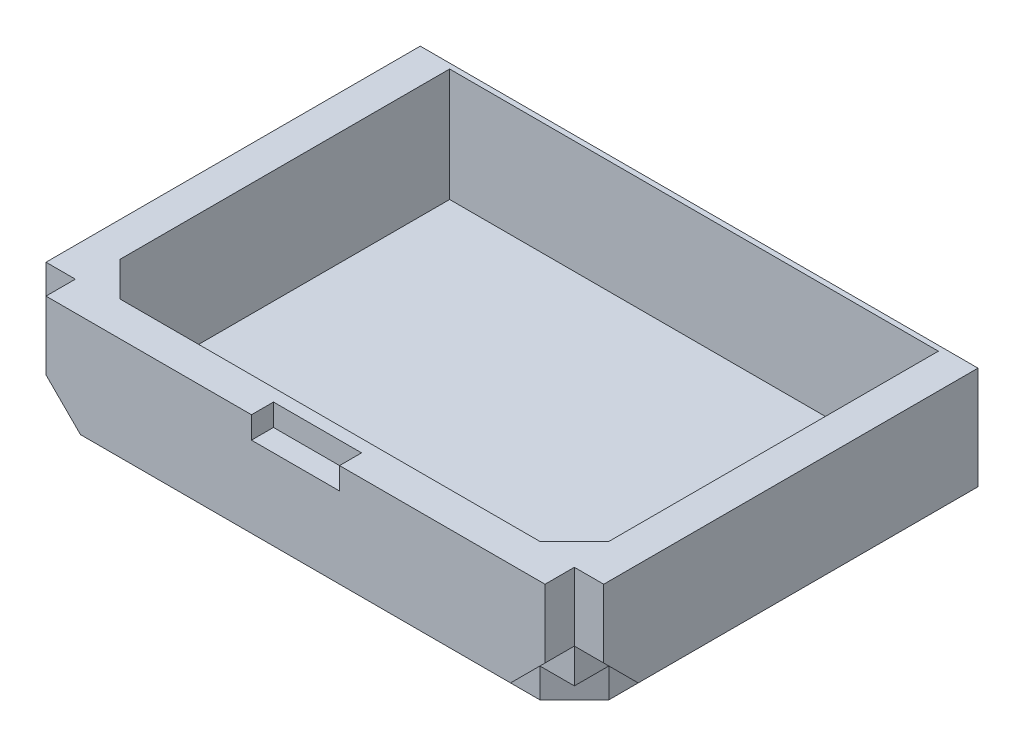
SolidWorks part; units mm, degrees
ref_plane "前基準面" through (0, 0, 0) normal (0, 0, 1) x (1, 0, 0)
ref_plane "上基準面" through (0, 0, 0) normal (0, 1, 0) x (1, 0, 0)
ref_plane "右基準面" through (0, 0, 0) normal (1, 0, 0) x (0, 0, -1)
sketch "草圖1" plane through (0, 0, 0) normal (0, 1, 0) x (1, 0, 0)
  line L1 (-190, -137.5) -> (190, -137.5)
  line L2 (-190, -137.5) -> (-190, 137.5)
  line L4 (190, -137.5) -> (190, 137.5)
  line L5 (-190, -137.5) -> (190, 137.5) construction
  line L6 (-190, 137.5) -> (190, -137.5) construction
  line L11 (-190, 137.5) -> (190, 137.5)
  point P0 (0, 0)
  dimension "D1" = 380
  dimension "D2" = 275
extrude "填料-伸長1" add sketch "草圖1" along normal blind 90
sketch "草圖2" plane through (0, 90, 0) normal (0, 1, 0) x (1, 0, 0)
  line L1 (-190, -137.5) -> (-170, -137.5)
  line L2 (-190, -137.5) -> (-190, -117.5)
  line L3 (-190, -117.5) -> (-170, -117.5)
  line L4 (-170, -137.5) -> (-170, -117.5)
  line L5 (190, -137.5) -> (170, -137.5)
  line L6 (190, -137.5) -> (190, -117.5)
  line L7 (190, -117.5) -> (170, -117.5)
  line L8 (170, -137.5) -> (170, -117.5)
  dimension "D1" = 20
  dimension "D2" = 20
  dimension "D3" = 20
  dimension "D4" = 20
extrude "除料-伸長1" cut sketch "草圖2" against normal up to vertex (90 mm away)
sketch "草圖4" plane through (0, 0, 117.5) normal (0, 0, 1) x (1, 0, 0)
  line L0 (-170, 0) -> (-170, 90) construction
  line L1 (-190, 0) -> (-170, 0)
  line L2 (-190, 0) -> (-190, 20)
  line L3 (-190, 20) -> (-170, 20)
  line L4 (-170, 0) -> (-170, 20)
  line L5 (190, 0) -> (190, 90) construction
  line L6 (170, 0) -> (190, 0)
  line L7 (170, 0) -> (170, 20)
  line L8 (170, 20) -> (190, 20)
  line L9 (190, 0) -> (190, 20)
  dimension "D1" = 20
  dimension "D2" = 20
extrude "除料-伸長3" cut sketch "草圖4" against normal up to vertex (255 mm away)
sketch "草圖5" plane through (-170, 0, 0) normal (-1, 0, 0) x (0, 0, 1)
  line L1 (137.5, 0) -> (117.5, 0)
  line L2 (137.5, 0) -> (137.5, 20)
  line L3 (137.5, 20) -> (117.5, 20)
  line L4 (117.5, 0) -> (117.5, 20)
extrude "除料-伸長4" cut sketch "草圖5" against normal up to vertex (340 mm away)
sketch "草圖6" plane through (0, 90, 0) normal (0, 1, 0) x (1, 0, 0)
  line L1 (-166.5, -114) -> (166.5, -114) construction
  line L2 (-166.5, -114) -> (-166.5, 134) construction
  line L4 (166.5, -114) -> (166.5, 134) construction
  line L5 (170, 137.5) -> (170, -117.5) construction
  line L7 (170, -117.5) -> (-170, -117.5) construction
  line L15 (-166.5, 134) -> (166.5, 134)
  line L16 (-170, 137.5) -> (-170, -117.5) construction
  line L18 (190, 137.5) -> (-190, 137.5) construction
  line L19 (-143, -114) -> (-166.5, -90.5)
  line L20 (0, -49.5) -> (0, 49.5) construction
  line L21 (143, -114) -> (166.5, -90.5)
  line L22 (-143, -114) -> (143, -114)
  line L23 (-166.5, 134) -> (-166.5, -90.5)
  line L24 (166.5, 134) -> (166.5, -90.5)
  dimension "D1" = 3.5
  dimension "D2" = 3.5
  dimension "D3" = 3.5
  dimension "D4" = 3.5
  dimension "D5" = 333
  dimension "D6" = 248
  dimension "D7" = 23.5
  dimension "D8" = 23.5
extrude "除料-伸長5" cut sketch "草圖6" against normal blind 77
sketch "草圖7" plane through (0, 0, 137.5) normal (0, 0, 1) x (1, 0, 0)
  line L0 (-170, 90) -> (170, 90) construction
  line L1 (-30, 90) -> (30, 90)
  line L2 (-30, 90) -> (-30, 75)
  line L3 (-30, 75) -> (30, 75)
  line L4 (30, 90) -> (30, 75)
  line L5 (0, -49.5) -> (0, 49.5) construction
  dimension "D1" = 60
  dimension "D2" = 15
  dimension "D3" = 30
extrude "除料-伸長6" cut sketch "草圖7" against normal blind 15
sketch "草圖9" plane through (0, 0, 137.5) normal (0, 0, 1) x (1, 0, 0)
  line L0 (-170, 20) -> (-170, 43.5)
  line L1 (-170, 20) -> (-170, 90) construction
  line L5 (170, 20) -> (-170, 20) construction
  line L6 (-146.5, 20) -> (-170, 20)
  line L14 (-170, 43.5) -> (-146.5, 20)
  line L15 (0, -49.5) -> (0, 49.5) construction
  line L16 (170, 43.5) -> (146.5, 20)
  line L17 (146.5, 20) -> (170, 20)
  line L18 (170, 20) -> (170, 43.5)
  dimension "D1" = 23.5
  dimension "D2" = 23.5
extrude "除料-伸長7" cut sketch "草圖9" against normal blind 20
sketch "草圖10" plane through (190, 0, 0) normal (1, 0, 0) x (0, 0, -1)
  line L0 (-94, 20) -> (-117.5, 20)
  line L1 (137.5, 20) -> (-117.5, 20) construction
  line L2 (-117.5, 20) -> (-117.5, 43.5)
  line L3 (-117.5, 20) -> (-117.5, 90) construction
  line L4 (-117.5, 43.5) -> (-94, 20)
  dimension "D1" = 23.5
  dimension "D2" = 23.5
extrude "除料-伸長8" cut sketch "草圖10" against normal blind 20
mirror "鏡射1" about plane through (0, 0, 0) normal (1, 0, 0) of "除料-伸長8"
sketch "草圖11" plane through (0, 0, 0) normal (0, -1, 0) x (1, 0, 0)
  line L0 (-146.5, 117.5) -> (-170, 117.5)
  line L1 (-170, 117.5) -> (-170, 94)
  line L2 (-170, 94) -> (-146.5, 117.5)
  line L3 (0, -49.5) -> (0, 49.5) construction
  line L4 (170, 94) -> (146.5, 117.5)
  line L5 (170, 117.5) -> (170, 94)
  line L6 (146.5, 117.5) -> (170, 117.5)
  dimension "D1" = 23.5
  dimension "D2" = 23.5
extrude "除料-伸長9" cut sketch "草圖11" against normal blind 20
equation "\"ˇ\"=3.30854"
